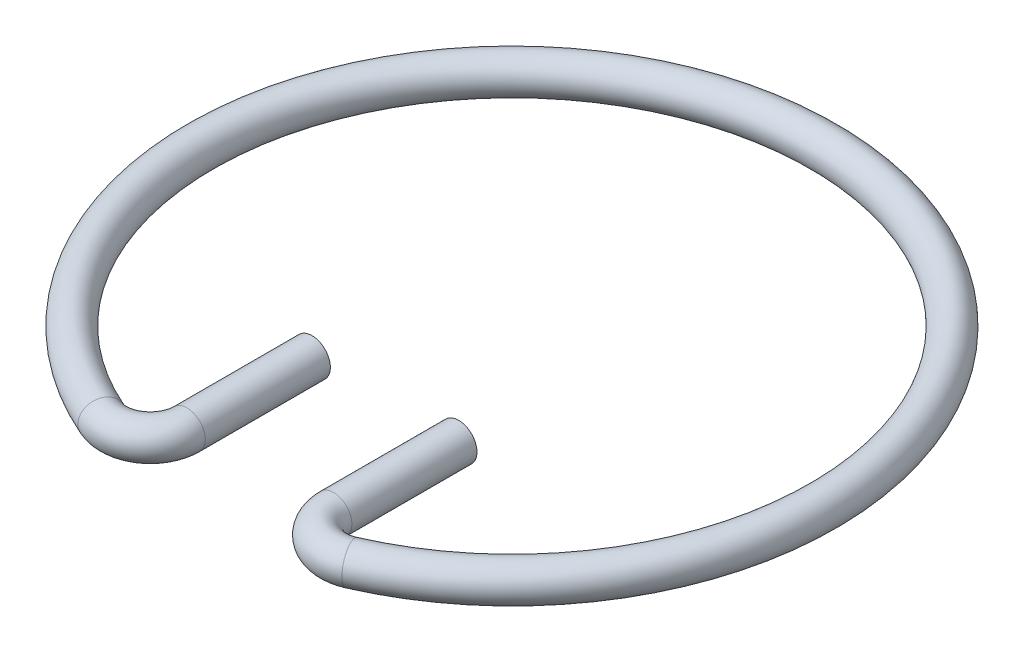
SolidWorks part; units mm, degrees
material "1060 Alloy"
ref_plane "Front Plane" through (0, 0, 0) normal (0, 0, 1) x (1, 0, 0)
ref_plane "Top Plane" through (0, 0, 0) normal (0, 1, 0) x (1, 0, 0)
ref_plane "Right Plane" through (0, 0, 0) normal (1, 0, 0) x (0, 0, -1)
sketch "Sketch1" plane through (0, 0, 0) normal (0, 0, 1) x (1, 0, 0)
  circle A0 centre (0, 0) radius 0.7937
  dimension "D1" = 1.5875
sketch "Sketch2" plane through (0, 0, 0) normal (0, 0, 1) x (1, 0, 0)
  line L0 (0, 0) -> (6.35, 0) construction
  circle A0 centre (6.35, 0) radius 0.7937
  circle A1 centre (0, 0) radius 0.7937 construction
  dimension "D1" = 6.35
sketch "Sketch3" plane through (0, 0, 0) normal (0, 1, 0) x (1, 0, 0)
  line L0 (3.175, 0) -> (3.175, 7.9526) construction
  line L1 (0, 0) -> (6.35, 0) construction
  line L2 (0, 0) -> (0, -5.4166)
  line L3 (6.35, 0) -> (6.35, -5.4166)
  line L4 (5.5563, 0) -> (7.1437, 0) construction
  arc A0 (-2.2232, -6.8712) -> (8.5732, -6.8712) centre (3.175, 5.4818) cw
  arc A1 (6.35, -5.4166) -> (8.5732, -6.8712) centre (7.9375, -5.4166) ccw
  arc A2 (0, -5.4166) -> (-2.2232, -6.8712) centre (-1.5875, -5.4166) cw
  point P14 (6.35, -7.62)
  dimension "D1" = 13.4811
  dimension "D3" = 1.5875
  dimension "D2" = 7.62
sweep "Sweep1" add profiles "Sketch1" path "Sketch3"
sketch "Sketch4" plane through (0, 0, 0) normal (0, 1, 0) x (1, 0, 0)
  circle A0 centre (3.175, 5.4818) radius 19.05
  arc A1 (8.891, -7.5986) -> (-2.541, -7.5986) centre (3.175, 5.4818) ccw construction
  arc A2 (8.891, -7.5986) -> (-2.541, -7.5986) centre (3.175, 5.4818) ccw
  dimension "D1" = 38.1
ref_plane "Plane1" through (0, 0.7937, 0) normal (0, 1, 0) x (1, 0, 0)
